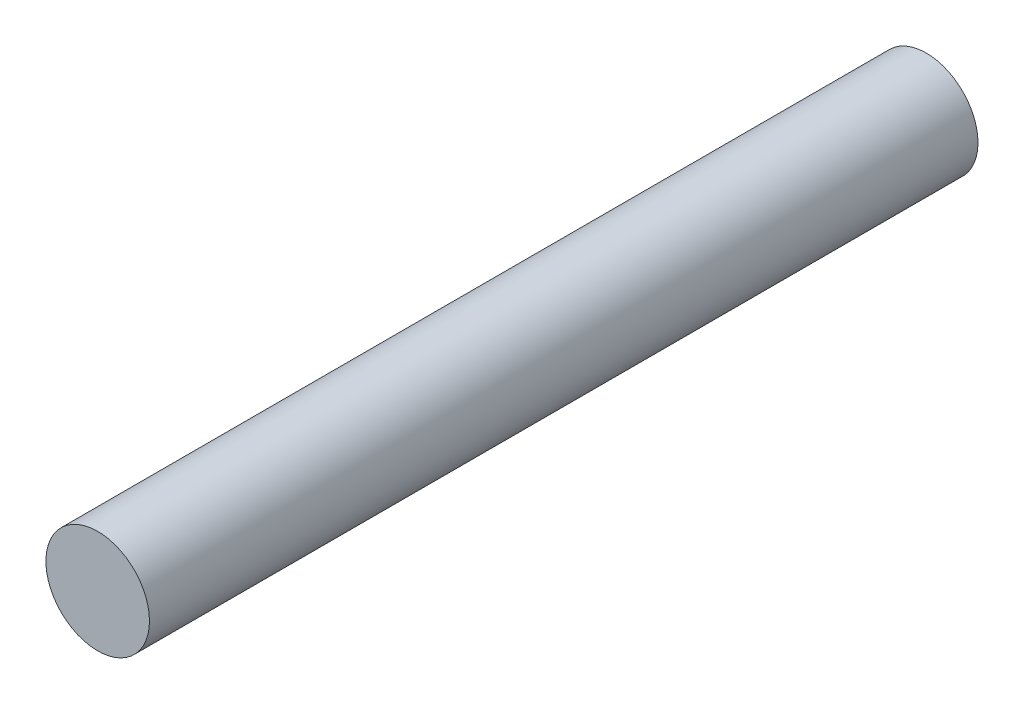
SolidWorks part; units mm, degrees
ref_plane "정면" through (0, 0, 0) normal (0, 0, 1) x (1, 0, 0)
ref_plane "윗면" through (0, 0, 0) normal (0, 1, 0) x (1, 0, 0)
ref_plane "우측면" through (0, 0, 0) normal (1, 0, 0) x (0, 0, -1)
sketch "스케치1" plane through (0, 0, 0) normal (0, 0, 1) x (1, 0, 0)
  circle A0 centre (0, 0) radius 3
  dimension "D1" = 6
extrude "보스-돌출1" add sketch "스케치1" along normal blind 48
